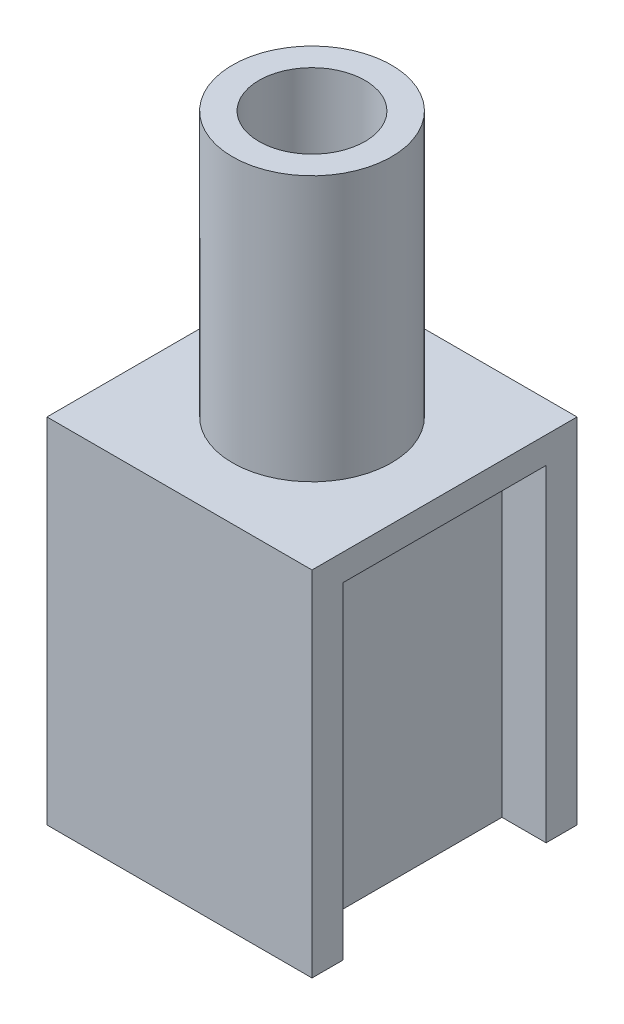
SolidWorks part; units mm, degrees
ref_plane "Front Plane" through (0, 0, 0) normal (0, 0, 1) x (1, 0, 0)
ref_plane "Top Plane" through (0, 0, 0) normal (0, 1, 0) x (1, 0, 0)
ref_plane "Right Plane" through (0, 0, 0) normal (1, 0, 0) x (0, 0, -1)
sketch "Sketch1" plane through (0, 0, 0) normal (0, 1, 0) x (1, 0, 0)
  line L1 (-15, -15) -> (15, -15)
  line L2 (-15, -15) -> (-15, 15)
  line L3 (-15, 15) -> (15, 15)
  line L4 (15, -15) -> (15, 15)
  line L5 (-15, -15) -> (15, 15) construction
  line L6 (-15, 15) -> (15, -15) construction
  point P0 (0, 0)
  dimension "D1" = 30
  dimension "D2" = 30
extrude "Boss-Extrude1" add sketch "Sketch1" along normal blind 40
sketch "Sketch2" plane through (0, 40, 0) normal (0, 1, 0) x (1, 0, 0)
  circle A1 centre (0, 0) radius 9
  dimension "D2" = 18
extrude "Boss-Extrude2" add sketch "Sketch2" along normal blind 30
sketch "Sketch3" plane through (0, 70, 0) normal (0, 1, 0) x (1, 0, 0)
  circle A0 centre (0, 0) radius 6
  dimension "D1" = 12
extrude "Cut-Extrude1" cut sketch "Sketch3" against normal blind 60
sketch "Sketch4" plane through (15, 0, 0) normal (1, 0, 0) x (0, 0, -1)
  line L0 (0, 0) -> (0, 54.4606) construction
  line L1 (-15, 40) -> (15, 40) construction
  line L2 (-11.5, 0) -> (11.5, 0)
  line L3 (-11.5, 0) -> (-11.5, 37)
  line L4 (-11.5, 37) -> (11.5, 37)
  line L5 (11.5, 0) -> (11.5, 37)
  line L6 (-11.5, 0) -> (11.5, 37) construction
  line L7 (-11.5, 37) -> (11.5, 0) construction
  line L8 (-15, 40) -> (-15, 0) construction
  line L12 (-15, 0) -> (15, 0) construction
  point P3 (0, 18.5)
  dimension "D1" = 3
  dimension "D2" = 3.5
extrude "Cut-Extrude2" cut sketch "Sketch4" against normal blind 5
sketch "Sketch5" plane through (-15, 0, 0) normal (-1, 0, 0) x (0, 0, 1)
  line L0 (-15, 40) -> (15, 40) construction
  line L1 (-11.5, 0) -> (11.5, 0)
  line L2 (-11.5, 0) -> (-11.5, 37)
  line L3 (-11.5, 37) -> (11.5, 37)
  line L4 (11.5, 0) -> (11.5, 37)
  line L5 (-11.5, 0) -> (11.5, 37) construction
  line L6 (-11.5, 37) -> (11.5, 0) construction
  line L7 (15, 40) -> (15, 0) construction
  line L8 (-15, 40) -> (-15, 0) construction
  line L9 (-15, 0) -> (15, 0) construction
  point P0 (0, 18.5)
  dimension "D1" = 3
  dimension "D2" = 3.5
  dimension "D3" = 3.5
extrude "Cut-Extrude3" cut sketch "Sketch5" against normal blind 5
